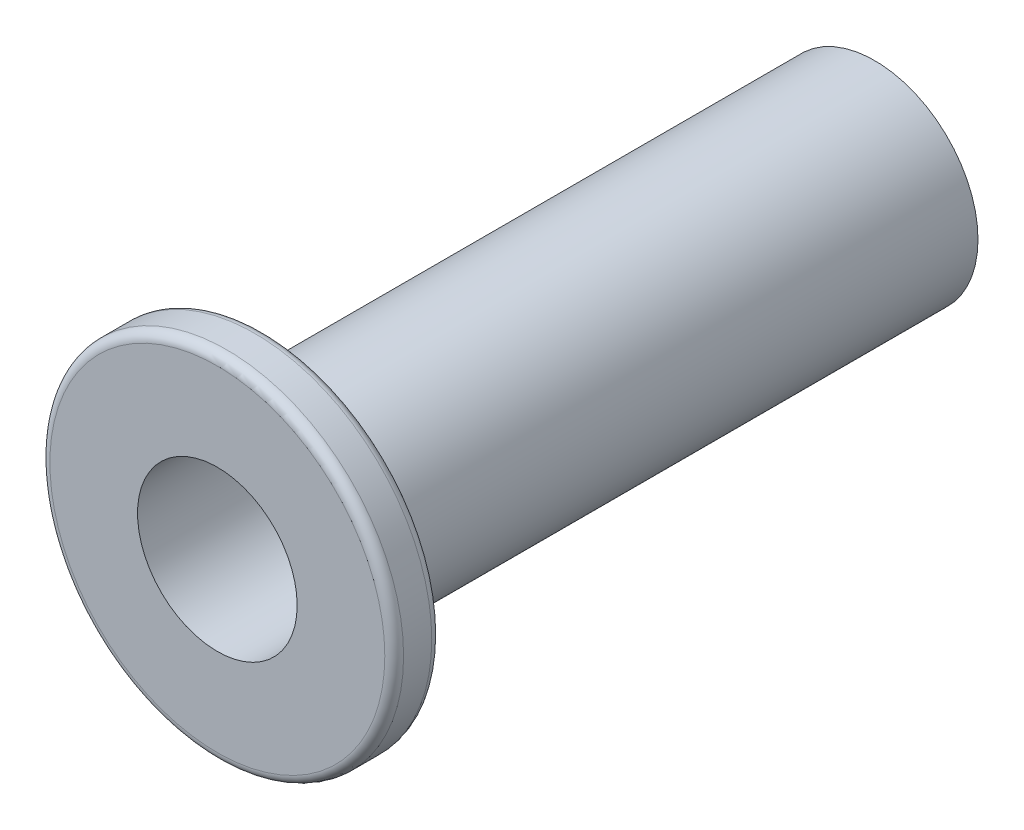
SolidWorks part; units mm, degrees
ref_plane "Plano frontal" through (0, 0, 0) normal (0, 0, 1) x (1, 0, 0)
ref_plane "Plano superior" through (0, 0, 0) normal (0, 1, 0) x (1, 0, 0)
ref_plane "Plano direito" through (0, 0, 0) normal (1, 0, 0) x (0, 0, -1)
sketch "Esboço1" plane through (0, 0, 0) normal (0, 0, 1) x (1, 0, 0)
  circle A0 centre (0, 0) radius 17
  circle A1 centre (0, 0) radius 22
  dimension "D1" = 34
  dimension "D2" = 5
extrude "Ressalto-extrusão1" add sketch "Esboço1" along normal blind 120
sketch "Esboço2" plane through (0, 0, 120) normal (0, 0, 1) x (1, 0, 0)
  circle A0 centre (0, 0) radius 37.6651
  circle A1 centre (0, 0) radius 17
  circle A2 centre (0, 0) radius 17 construction
extrude "Ressalto-extrusão2" add sketch "Esboço2" along normal blind 10
fillet "Filete1" radius 10 1 edges at (22, 0, 120)
fillet "Filete2" radius 2 2 edges at (37.6651, 0, 130) (37.6651, 0, 120)
sketch "Esboço3" plane through (0, 0, 0) normal (0, 0, -1) x (-1, 0, 0)
  circle A0 centre (0, 0) radius 22
  circle A1 centre (0, 0) radius 22 construction
extrude "Ressalto-extrusão3" add sketch "Esboço3" along normal blind 10
